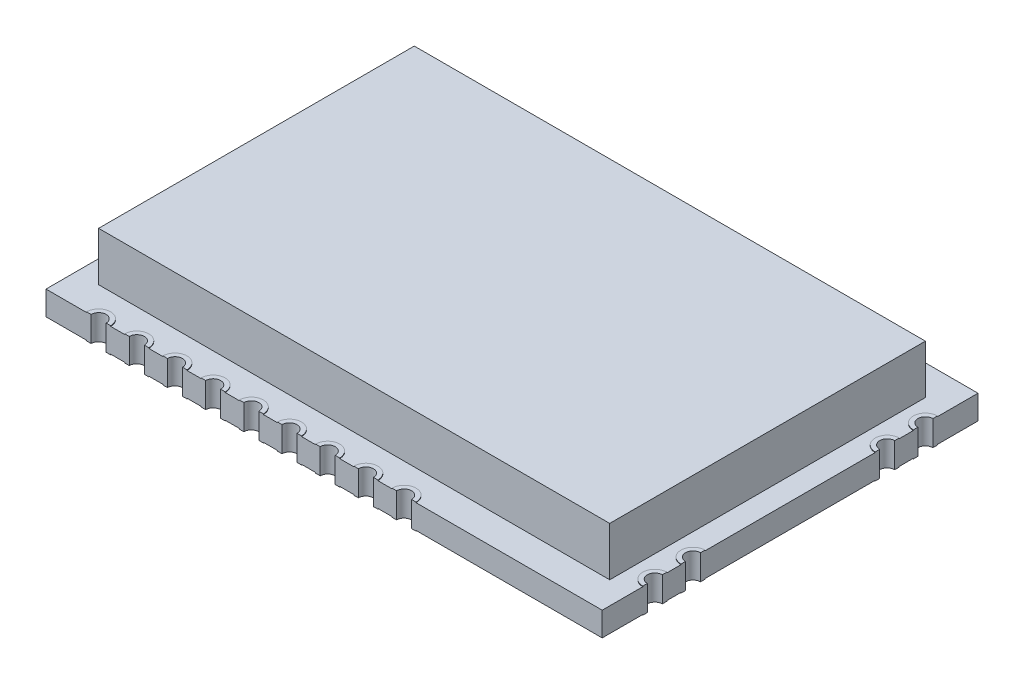
SolidWorks part; units mm, degrees
ref_plane "Front Plane" through (0, 0, 0) normal (0, 0, 1) x (1, 0, 0)
ref_plane "Top Plane" through (0, 0, 0) normal (0, 1, 0) x (1, 0, 0)
ref_plane "Right Plane" through (0, 0, 0) normal (1, 0, 0) x (0, 0, -1)
sketch "Sketch1" plane through (0, 0, 0) normal (0, 1, 0) x (1, 0, 0)
  line L1 (18.5, 12.5) -> (-18.5, 12.5)
  line L2 (18.5, 12.5) -> (18.5, -12.5)
  line L3 (18.5, -12.5) -> (-18.5, -12.5)
  line L4 (-18.5, 12.5) -> (-18.5, -12.5)
  circle A0 centre (-15, 12.5) radius 0.5
  circle A1 centre (-12.46, 12.5) radius 0.5
  circle A2 centre (-9.92, 12.5) radius 0.5
  circle A3 centre (-7.38, 12.5) radius 0.5
  circle A4 centre (-4.84, 12.5) radius 0.5
  circle A5 centre (-2.3, 12.5) radius 0.5
  circle A7 centre (0.24, 12.5) radius 0.5
  circle A8 centre (2.78, 12.5) radius 0.5
  circle A9 centre (5.32, 12.5) radius 0.5
  circle A10 centre (-15, -12.5) radius 0.5
  circle A11 centre (-12.46, -12.5) radius 0.5
  circle A12 centre (-9.92, -12.5) radius 0.5
  circle A13 centre (-7.38, -12.5) radius 0.5
  circle A14 centre (-4.84, -12.5) radius 0.5
  circle A15 centre (-2.3, -12.5) radius 0.5
  circle A16 centre (0.24, -12.5) radius 0.5
  circle A17 centre (2.78, -12.5) radius 0.5
  circle A18 centre (5.32, -12.5) radius 0.5
  circle A19 centre (18.5, -9) radius 0.5
  circle A20 centre (18.5, -6.46) radius 0.5
  circle A21 centre (18.5, 6.46) radius 0.5
  circle A22 centre (18.5, 9) radius 0.5
  dimension "D5" = 1
  dimension "D1" = 37
  dimension "D2" = 25
  dimension "D3" = 18.5
  dimension "D4" = 12.5
  dimension "D6" = 3.5
  dimension "D7" = 2.54
  dimension "D8" = 2.54
  dimension "D9" = 2.54
  dimension "D10" = 2.54
  dimension "D11" = 2.54
  dimension "D12" = 2.54
  dimension "D13" = 2.54
  dimension "D14" = 2.54
  dimension "D15" = 3.5
  dimension "D16" = 2.54
  dimension "D17" = 3.5
  dimension "D18" = 2.54
  dimension "D19" = 3.5
  dimension "D20" = 2.54
  dimension "D21" = 2.54
  dimension "D22" = 2.54
  dimension "D23" = 2.54
  dimension "D24" = 2.54
  dimension "D25" = 2.54
  dimension "D26" = 2.54
  dimension "D27" = 2.54
extrude "Boss-Extrude1" add sketch "Sketch1" along normal blind 1.6 contours A22 L2 L1 A9 A8 A7 A5 A4 A3 A2 A1 A0 L4 L3 A10 A11 A12 A13 A14 A15 A16 A17 A18 A19 A20 A21
sketch "Sketch2" plane through (0, 1.6, 0) normal (0, 1, 0) x (1, 0, 0)
  line L0 (-15.5, 12.5) -> (-15.8, 12.5)
  line L1 (-14.5, 12.5) -> (-14.2, 12.5)
  line L2 (18.5, -9.5) -> (18.5, -12.5) construction
  line L3 (-13.26, 12.5) -> (-12.96, 12.5)
  line L4 (-11.96, 12.5) -> (-11.66, 12.5)
  line L5 (5.82, 12.5) -> (6.12, 12.5)
  line L6 (4.82, 12.5) -> (4.52, 12.5)
  line L7 (3.58, 12.5) -> (3.28, 12.5)
  line L8 (0.74, 12.5) -> (1.04, 12.5)
  line L9 (-0.56, 12.5) -> (-0.26, 12.5)
  line L10 (-3.1, 12.5) -> (-2.8, 12.5)
  line L11 (-1.5, 12.5) -> (-1.8, 12.5)
  line L12 (-5.64, 12.5) -> (-5.34, 12.5)
  line L13 (-4.34, 12.5) -> (-4.04, 12.5)
  line L14 (-6.88, 12.5) -> (-6.58, 12.5)
  line L15 (-8.18, 12.5) -> (-7.88, 12.5)
  line L16 (-10.72, 12.5) -> (-10.42, 12.5)
  line L17 (-9.42, 12.5) -> (-9.12, 12.5)
  line L18 (1.98, 12.5) -> (2.28, 12.5)
  line L21 (5.82, -12.5) -> (6.12, -12.5)
  line L22 (4.82, -12.5) -> (4.52, -12.5)
  line L23 (3.28, -12.5) -> (3.58, -12.5)
  line L24 (2.28, -12.5) -> (1.98, -12.5)
  line L25 (-0.56, -12.5) -> (-0.26, -12.5)
  line L26 (0.74, -12.5) -> (1.04, -12.5)
  line L27 (-3.1, -12.5) -> (-2.8, -12.5)
  line L28 (-1.8, -12.5) -> (-1.5, -12.5)
  line L29 (-5.64, -12.5) -> (-5.34, -12.5)
  line L30 (-4.34, -12.5) -> (-4.04, -12.5)
  line L31 (-8.18, -12.5) -> (-7.88, -12.5)
  line L32 (-6.88, -12.5) -> (-6.58, -12.5)
  line L33 (-10.72, -12.5) -> (-10.42, -12.5)
  line L34 (-9.42, -12.5) -> (-9.12, -12.5)
  line L35 (-13.26, -12.5) -> (-12.96, -12.5)
  line L36 (-11.96, -12.5) -> (-11.66, -12.5)
  line L37 (18.5, -8.2) -> (18.5, -8.5)
  line L38 (18.5, 5.96) -> (18.5, -5.96) construction
  line L39 (18.5, 9.8) -> (18.5, 9.5)
  line L40 (18.5, 8.5) -> (18.5, 8.2)
  line L41 (18.5, 7.26) -> (18.5, 6.96)
  line L42 (18.5, 5.96) -> (18.5, 5.66)
  line L43 (18.5, -5.66) -> (18.5, -5.96)
  line L44 (18.5, -6.96) -> (18.5, -7.26)
  line L46 (18.5, -9.5) -> (18.5, -9.8)
  line L47 (18.5, -12.5) -> (5.82, -12.5) construction
  line L48 (4.82, -12.5) -> (3.28, -12.5) construction
  line L49 (2.28, -12.5) -> (0.74, -12.5) construction
  line L50 (-0.26, -12.5) -> (-1.8, -12.5) construction
  line L51 (-2.8, -12.5) -> (-4.34, -12.5) construction
  line L52 (-5.34, -12.5) -> (-6.88, -12.5) construction
  line L53 (-7.88, -12.5) -> (-9.42, -12.5) construction
  line L54 (-10.42, -12.5) -> (-11.96, -12.5) construction
  line L58 (-12.96, -12.5) -> (-14.5, -12.5) construction
  line L59 (-15.5, -12.5) -> (-18.5, -12.5) construction
  line L60 (-15.5, -12.5) -> (-15.8, -12.5)
  line L61 (-14.5, -12.5) -> (-14.2, -12.5)
  arc A1 (-15.8, 12.5) -> (-14.2, 12.5) centre (-15, 12.5) ccw
  arc A3 (-13.26, 12.5) -> (-11.66, 12.5) centre (-12.46, 12.5) ccw
  arc A4 (-10.72, 12.5) -> (-9.12, 12.5) centre (-9.92, 12.5) ccw
  arc A5 (-8.18, 12.5) -> (-6.58, 12.5) centre (-7.38, 12.5) ccw
  arc A6 (-5.64, 12.5) -> (-4.04, 12.5) centre (-4.84, 12.5) ccw
  arc A7 (-0.56, 12.5) -> (1.04, 12.5) centre (0.24, 12.5) ccw
  arc A8 (1.98, 12.5) -> (3.58, 12.5) centre (2.78, 12.5) ccw
  arc A9 (4.52, 12.5) -> (6.12, 12.5) centre (5.32, 12.5) ccw
  arc A11 (-3.1, 12.5) -> (-1.5, 12.5) centre (-2.3, 12.5) ccw
  arc A12 (-11.66, -12.5) -> (-13.26, -12.5) centre (-12.46, -12.5) ccw
  arc A14 (-9.12, -12.5) -> (-10.72, -12.5) centre (-9.92, -12.5) ccw
  arc A15 (-6.58, -12.5) -> (-8.18, -12.5) centre (-7.38, -12.5) ccw
  arc A16 (-4.04, -12.5) -> (-5.64, -12.5) centre (-4.84, -12.5) ccw
  arc A17 (-1.5, -12.5) -> (-3.1, -12.5) centre (-2.3, -12.5) ccw
  arc A18 (1.04, -12.5) -> (-0.56, -12.5) centre (0.24, -12.5) ccw
  arc A19 (3.58, -12.5) -> (1.98, -12.5) centre (2.78, -12.5) ccw
  arc A20 (6.12, -12.5) -> (4.52, -12.5) centre (5.32, -12.5) ccw
  arc A21 (18.5, -5.66) -> (18.5, -7.26) centre (18.5, -6.46) ccw
  arc A22 (18.5, -8.2) -> (18.5, -9.8) centre (18.5, -9) ccw
  arc A23 (18.5, 7.26) -> (18.5, 5.66) centre (18.5, 6.46) ccw
  arc A24 (18.5, 9.8) -> (18.5, 8.2) centre (18.5, 9) ccw
  arc A25 (-15.5, 12.5) -> (-14.5, 12.5) centre (-15, 12.5) ccw
  arc A26 (-15.5, 12.5) -> (-14.5, 12.5) centre (-15, 12.5) ccw construction
  arc A27 (-12.96, 12.5) -> (-11.96, 12.5) centre (-12.46, 12.5) ccw
  arc A28 (-10.42, 12.5) -> (-9.42, 12.5) centre (-9.92, 12.5) ccw
  arc A29 (-7.88, 12.5) -> (-6.88, 12.5) centre (-7.38, 12.5) ccw
  arc A30 (-5.34, 12.5) -> (-4.34, 12.5) centre (-4.84, 12.5) ccw
  arc A31 (-2.8, 12.5) -> (-1.8, 12.5) centre (-2.3, 12.5) ccw
  arc A32 (-0.26, 12.5) -> (0.74, 12.5) centre (0.24, 12.5) ccw
  arc A33 (2.28, 12.5) -> (3.28, 12.5) centre (2.78, 12.5) ccw
  arc A34 (4.82, 12.5) -> (5.82, 12.5) centre (5.32, 12.5) ccw
  arc A36 (-14.5, -12.5) -> (-15.5, -12.5) centre (-15, -12.5) ccw construction
  arc A37 (-11.96, -12.5) -> (-12.96, -12.5) centre (-12.46, -12.5) ccw
  arc A38 (-9.42, -12.5) -> (-10.42, -12.5) centre (-9.92, -12.5) ccw
  arc A39 (-6.88, -12.5) -> (-7.88, -12.5) centre (-7.38, -12.5) ccw
  arc A40 (-4.34, -12.5) -> (-5.34, -12.5) centre (-4.84, -12.5) ccw
  arc A41 (-1.8, -12.5) -> (-2.8, -12.5) centre (-2.3, -12.5) ccw
  arc A42 (0.74, -12.5) -> (-0.26, -12.5) centre (0.24, -12.5) ccw
  arc A43 (3.28, -12.5) -> (2.28, -12.5) centre (2.78, -12.5) ccw
  arc A44 (5.82, -12.5) -> (4.82, -12.5) centre (5.32, -12.5) ccw
  arc A47 (18.5, -6.96) -> (18.5, -5.96) centre (18.5, -6.46) cw
  arc A48 (18.5, 5.96) -> (18.5, 6.96) centre (18.5, 6.46) cw
  arc A49 (18.5, 8.5) -> (18.5, 9.5) centre (18.5, 9) cw
  arc A51 (18.5, -9.5) -> (18.5, -8.5) centre (18.5, -9) cw
  arc A53 (-15.5, -12.5) -> (-14.5, -12.5) centre (-15, -12.5) cw
  arc A54 (-14.2, -12.5) -> (-15.8, -12.5) centre (-15, -12.5) ccw
  dimension "D1" = 0.8
  dimension "D2" = 0.8
  dimension "D3" = 0.8
  dimension "D4" = 0.8
  dimension "D6" = 0.8
  dimension "D5" = 0.8
  dimension "D7" = 0.8
  dimension "D8" = 0.8
  dimension "D9" = 0.8
  dimension "D10" = 0.8
  dimension "D11" = 0.8
  dimension "D12" = 0.8
  dimension "D13" = 0.8
  dimension "D14" = 0.8
extrude "Boss-Extrude2" add sketch "Sketch2" along normal blind 0.04
sketch "Sketch9" plane through (0, 0, 0) normal (0, -1, 0) x (-1, 0, 0)
  line L0 (15.5, 12.5) -> (15.8, 12.5)
  line L1 (15.5, 12.5) -> (18.5, 12.5) construction
  line L2 (15.8, 12.5) -> (15.8, 10.505)
  line L3 (15.8, 10.505) -> (14.2, 10.505)
  line L4 (14.2, 10.505) -> (14.2, 12.5)
  line L5 (12.96, 12.5) -> (14.5, 12.5) construction
  line L7 (12.96, 12.5) -> (13.26, 12.5)
  line L8 (13.26, 12.5) -> (13.26, 10.505)
  line L9 (13.26, 10.505) -> (11.66, 10.505)
  line L10 (11.66, 10.505) -> (11.66, 12.5)
  line L11 (11.66, 12.5) -> (11.96, 12.5)
  line L12 (10.42, 12.5) -> (10.72, 12.5)
  line L13 (10.72, 12.5) -> (10.72, 10.505)
  line L14 (10.72, 10.505) -> (9.12, 10.505)
  line L15 (9.12, 10.505) -> (9.12, 12.5)
  line L16 (9.12, 12.5) -> (9.42, 12.5)
  line L17 (10.42, 12.5) -> (11.96, 12.5) construction
  line L18 (7.88, 12.5) -> (8.18, 12.5)
  line L19 (8.18, 12.5) -> (8.18, 10.505)
  line L20 (8.18, 10.505) -> (6.58, 10.505)
  line L21 (6.58, 10.505) -> (6.58, 12.5)
  line L22 (6.58, 12.5) -> (6.88, 12.5)
  line L23 (7.88, 12.5) -> (9.42, 12.5) construction
  line L24 (5.34, 12.5) -> (5.64, 12.5)
  line L25 (5.64, 12.5) -> (5.64, 10.505)
  line L26 (5.64, 10.505) -> (4.04, 10.505)
  line L27 (4.04, 10.505) -> (4.04, 12.5)
  line L28 (4.04, 12.5) -> (4.34, 12.5)
  line L29 (2.8, 12.5) -> (3.1, 12.5)
  line L30 (3.1, 12.5) -> (3.1, 10.505)
  line L31 (3.1, 10.505) -> (1.5, 10.505)
  line L32 (1.5, 10.505) -> (1.5, 12.5)
  line L33 (1.5, 12.5) -> (1.8, 12.5)
  line L34 (0.26, 12.5) -> (0.56, 12.5)
  line L35 (0.56, 12.5) -> (0.56, 10.505)
  line L36 (0.56, 10.505) -> (-1.04, 10.505)
  line L37 (-1.04, 10.505) -> (-1.04, 12.5)
  line L38 (-1.04, 12.5) -> (-0.74, 12.5)
  line L39 (-2.28, 12.5) -> (-1.98, 12.5)
  line L40 (-1.98, 12.5) -> (-1.98, 10.505)
  line L41 (-1.98, 10.505) -> (-3.58, 10.505)
  line L42 (-3.58, 10.505) -> (-3.58, 12.5)
  line L43 (-3.58, 12.5) -> (-3.28, 12.5)
  line L44 (-4.82, 12.5) -> (-4.52, 12.5)
  line L45 (-4.52, 12.5) -> (-4.52, 10.505)
  line L46 (-4.52, 10.505) -> (-6.12, 10.505)
  line L47 (-6.12, 10.505) -> (-6.12, 12.5)
  line L48 (-6.12, 12.5) -> (-5.82, 12.5)
  line L50 (15.8, -12.5) -> (15.8, -10.5)
  line L51 (15.8, -10.5) -> (14.2, -10.5)
  line L54 (12.96, -12.5) -> (13.26, -12.5)
  line L55 (13.26, -12.5) -> (13.26, -10.5)
  line L56 (13.26, -10.5) -> (11.66, -10.5)
  line L57 (11.66, -10.5) -> (11.66, -12.5)
  line L58 (11.66, -12.5) -> (11.96, -12.5)
  line L59 (10.42, -12.5) -> (10.72, -12.5)
  line L60 (10.72, -12.5) -> (10.72, -10.5)
  line L61 (10.72, -10.5) -> (9.12, -10.5)
  line L62 (9.12, -10.5) -> (9.12, -12.5)
  line L63 (9.12, -12.5) -> (9.42, -12.5)
  line L64 (7.88, -12.5) -> (9.42, -12.5) construction
  line L65 (7.88, -12.5) -> (8.18, -12.5)
  line L66 (8.18, -12.5) -> (8.18, -10.5)
  line L67 (8.18, -10.5) -> (6.5819, -10.5)
  line L68 (6.5819, -10.5) -> (6.58, -12.5)
  line L69 (6.58, -12.5) -> (6.88, -12.5)
  line L70 (5.34, -12.5) -> (5.64, -12.5)
  line L71 (5.64, -12.5) -> (5.64, -10.5)
  line L72 (5.64, -10.5) -> (4.04, -10.5)
  line L73 (4.04, -10.5) -> (4.04, -12.5)
  line L74 (4.04, -12.5) -> (4.34, -12.5)
  line L75 (5.34, -12.5) -> (6.88, -12.5) construction
  line L76 (2.8, -12.5) -> (3.1, -12.5)
  line L77 (3.1, -12.5) -> (3.1, -10.5)
  line L78 (3.1, -10.5) -> (1.5, -10.5)
  line L79 (1.5, -10.5) -> (1.5, -12.5)
  line L80 (1.5, -12.5) -> (1.8, -12.5)
  line L81 (0.26, -12.5) -> (1.8, -12.5) construction
  line L82 (0.26, -12.5) -> (0.56, -12.5)
  line L83 (0.56, -12.5) -> (0.56, -10.5)
  line L84 (0.56, -10.5) -> (-1.04, -10.5)
  line L85 (-1.04, -10.5) -> (-1.04, -12.5)
  line L86 (-1.04, -12.5) -> (-0.74, -12.5)
  line L87 (-2.28, -12.5) -> (-0.74, -12.5) construction
  line L88 (-2.28, -12.5) -> (-1.98, -12.5)
  line L89 (-1.98, -12.5) -> (-1.98, -10.5)
  line L90 (-1.98, -10.5) -> (-3.58, -10.5)
  line L91 (-3.58, -10.5) -> (-3.58, -12.5)
  line L92 (-3.58, -12.5) -> (-3.28, -12.5)
  line L93 (-4.82, -12.5) -> (-3.28, -12.5) construction
  line L94 (-4.82, -12.5) -> (-4.52, -12.5)
  line L95 (-4.52, -12.5) -> (-4.52, -10.5)
  line L96 (-4.52, -10.5) -> (-6.0665, -10.5)
  line L97 (-6.0665, -10.5) -> (-6.12, -12.5)
  line L98 (-6.12, -12.5) -> (-5.82, -12.5)
  line L99 (-18.5, -12.5) -> (-5.82, -12.5) construction
  line L100 (-18.5, 9.5) -> (-18.5, 9.8)
  line L101 (-18.5, 12.5) -> (-18.5, 9.5) construction
  line L102 (-18.5, 9.8) -> (-16.5, 9.8)
  line L103 (-16.5, 9.8) -> (-16.5, 8.2)
  line L104 (-16.5, 8.2) -> (-18.5, 8.2)
  line L105 (-18.5, 8.5) -> (-18.5, 6.96) construction
  line L106 (-18.5, 8.2) -> (-18.5, 8.5)
  line L107 (-18.5, 6.96) -> (-18.5, 7.26)
  line L108 (-18.5, 7.26) -> (-16.5, 7.26)
  line L109 (-16.5, 7.26) -> (-16.5, 5.66)
  line L110 (-16.5, 5.66) -> (-18.5, 5.66)
  line L111 (-18.5, 5.66) -> (-18.5, 5.96)
  line L112 (-18.5, 5.96) -> (-18.5, -5.96) construction
  line L113 (-18.5, -5.96) -> (-18.5, -5.66)
  line L114 (-18.5, -5.66) -> (-16.5, -5.66)
  line L115 (-16.5, -5.66) -> (-16.5, -7.26)
  line L116 (-16.5, -7.26) -> (-18.5, -7.26)
  line L117 (-18.5, -7.26) -> (-18.5, -6.96)
  line L118 (-18.5, -8.5) -> (-18.5, -8.2)
  line L119 (-18.5, -8.2) -> (-16.5, -8.2)
  line L120 (-16.5, -8.2) -> (-16.5, -9.8)
  line L121 (-16.5, -9.8) -> (-18.5, -9.8)
  line L122 (-18.5, -9.8) -> (-18.5, -9.5)
  line L123 (14.5, 12.5) -> (14.2, 12.5)
  line L124 (14.5, -12.5) -> (14.2, -12.5)
  line L125 (12.96, -12.5) -> (14.5, -12.5) construction
  line L126 (14.2, -12.5) -> (14.2, -10.5)
  line L127 (15.5, -12.5) -> (15.8, -12.5)
  arc A0 (11.96, 12.5) -> (12.96, 12.5) centre (12.46, 12.5) ccw
  arc A2 (14.5, 12.5) -> (15.5, 12.5) centre (15, 12.5) ccw construction
  arc A3 (9.42, 12.5) -> (10.42, 12.5) centre (9.92, 12.5) ccw
  arc A4 (6.88, 12.5) -> (7.88, 12.5) centre (7.38, 12.5) ccw
  arc A5 (6.88, 12.5) -> (7.88, 12.5) centre (7.38, 12.5) ccw construction
  arc A6 (4.34, 12.5) -> (5.34, 12.5) centre (4.84, 12.5) ccw
  arc A7 (1.8, 12.5) -> (2.8, 12.5) centre (2.3, 12.5) ccw
  arc A8 (-0.74, 12.5) -> (0.26, 12.5) centre (-0.24, 12.5) ccw
  arc A9 (-3.28, 12.5) -> (-2.28, 12.5) centre (-2.78, 12.5) ccw
  arc A10 (-5.82, 12.5) -> (-4.82, 12.5) centre (-5.32, 12.5) ccw
  arc A12 (15.5, -12.5) -> (14.5, -12.5) centre (15, -12.5) ccw construction
  arc A13 (12.96, -12.5) -> (11.96, -12.5) centre (12.46, -12.5) ccw
  arc A14 (10.42, -12.5) -> (9.42, -12.5) centre (9.92, -12.5) ccw
  arc A15 (7.88, -12.5) -> (6.88, -12.5) centre (7.38, -12.5) ccw
  arc A16 (5.34, -12.5) -> (4.34, -12.5) centre (4.84, -12.5) ccw
  arc A17 (2.8, -12.5) -> (1.8, -12.5) centre (2.3, -12.5) ccw
  arc A18 (0.26, -12.5) -> (-0.74, -12.5) centre (-0.24, -12.5) ccw
  arc A19 (-2.28, -12.5) -> (-3.28, -12.5) centre (-2.78, -12.5) ccw
  arc A20 (-4.82, -12.5) -> (-5.82, -12.5) centre (-5.32, -12.5) ccw
  arc A21 (-18.5, 9.5) -> (-18.5, 8.5) centre (-18.5, 9) cw
  arc A22 (-18.5, 8.5) -> (-18.5, 9.5) centre (-18.5, 9) ccw construction
  arc A23 (-18.5, 6.96) -> (-18.5, 5.96) centre (-18.5, 6.46) cw
  arc A24 (-18.5, -5.96) -> (-18.5, -6.96) centre (-18.5, -6.46) cw
  arc A25 (-18.5, -8.5) -> (-18.5, -9.5) centre (-18.5, -9) cw
  arc A26 (-18.5, -9.5) -> (-18.5, -8.5) centre (-18.5, -9) ccw construction
  arc A27 (-18.5, -6.96) -> (-18.5, -5.96) centre (-18.5, -6.46) ccw construction
  arc A28 (14.5, 12.5) -> (15.5, 12.5) centre (15, 12.5) ccw
  arc A29 (15.5, -12.5) -> (14.5, -12.5) centre (15, -12.5) ccw
  point P3 (1.229, -12.5)
  point P28 (1.229, -10.5)
  point P174 (-1.04, -12.5)
  point P190 (-1.04, -10.5)
  point P230 (1.5, -12.5)
  point P238 (1.5, -10.5)
  point P240 (-6.12, -12.5)
  point P243 (-6.0684, -10.5738)
  point P245 (-3.58, -12.5)
  point P265 (-3.58, -10.6361)
  point P267 (-1.98, -10.5)
  point P270 (-4.52, -10.5)
  dimension "D1" = 0.3
  dimension "D2" = 0.3
  dimension "D4" = 1.6
  dimension "D5" = 0.3
  dimension "D6" = 0.3
  dimension "D7" = 2
  dimension "D8" = 1.6
  dimension "D9" = 2
  dimension "D10" = 0.3
  dimension "D11" = 0.3
extrude "Boss-Extrude3" add sketch "Sketch9" along normal blind 0.04
sketch "Sketch11" plane through (0, 1.6, 0) normal (0, 1, 0) x (1, 0, 0)
  line L0 (-15.8, -12.5) -> (-18.5, -12.5) construction
  line L1 (-17, 10.5) -> (17, 10.5)
  line L2 (-17, 10.5) -> (-17, -10.5)
  line L3 (-17, -10.5) -> (17, -10.5)
  line L4 (17, 10.5) -> (17, -10.5)
  line L5 (-18.5, 12.5) -> (-18.5, -12.5) construction
  dimension "D1" = 21
  dimension "D2" = 2
  dimension "D3" = 1.5
  dimension "D4" = 34
extrude "Boss-Extrude5" add sketch "Sketch11" along normal blind 3.25
